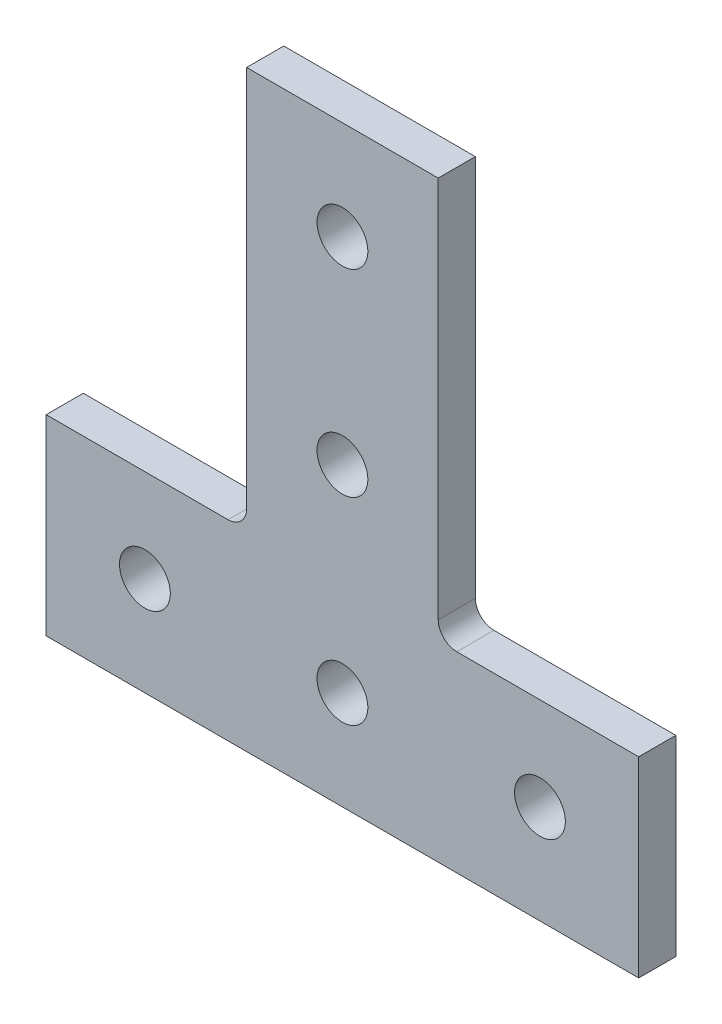
SolidWorks part; units mm, degrees
ref_plane "Front Plane" through (0, 0, 0) normal (0, 0, 1) x (1, 0, 0)
ref_plane "Top Plane" through (0, 0, 0) normal (0, 1, 0) x (1, 0, 0)
ref_plane "Right Plane" through (0, 0, 0) normal (1, 0, 0) x (0, 0, -1)
ref_plane "Plane1" through (0, 0, 4.7752) normal (0, 0, 1) x (1, 0, 0)
sketch "Sketch1" plane through (0, 0, 4.7752) normal (0, 0, 1) x (1, 0, 0)
  line L0 (-14.7066, 24.638) -> (-38.1, 24.638)
  line L1 (-38.1, 24.638) -> (-38.1, 0)
  line L2 (-38.1, 0) -> (38.1, 0)
  line L3 (38.1, 0) -> (38.1, 24.638)
  line L4 (38.1, 24.638) -> (14.7066, 24.638)
  line L5 (12.319, 27.0256) -> (12.319, 76.2)
  line L6 (12.319, 76.2) -> (-12.319, 76.2)
  line L7 (-12.319, 76.2) -> (-12.319, 27.0256)
  circle A0 centre (-25.4, 12.7) radius 3.2639
  circle A1 centre (0, 38.1) radius 3.2639
  circle A2 centre (0, 63.5) radius 3.2639
  circle A3 centre (0, 12.7) radius 3.2639
  circle A4 centre (25.4, 12.7) radius 3.2639
  arc A5 (14.7066, 24.638) -> (12.319, 27.0256) centre (14.7066, 27.0256) cw
  arc A6 (-12.319, 27.0256) -> (-14.7066, 24.638) centre (-14.7066, 27.0256) cw
extrude "Boss-Extrude1" add sketch "Sketch1" against normal blind 4.7752
